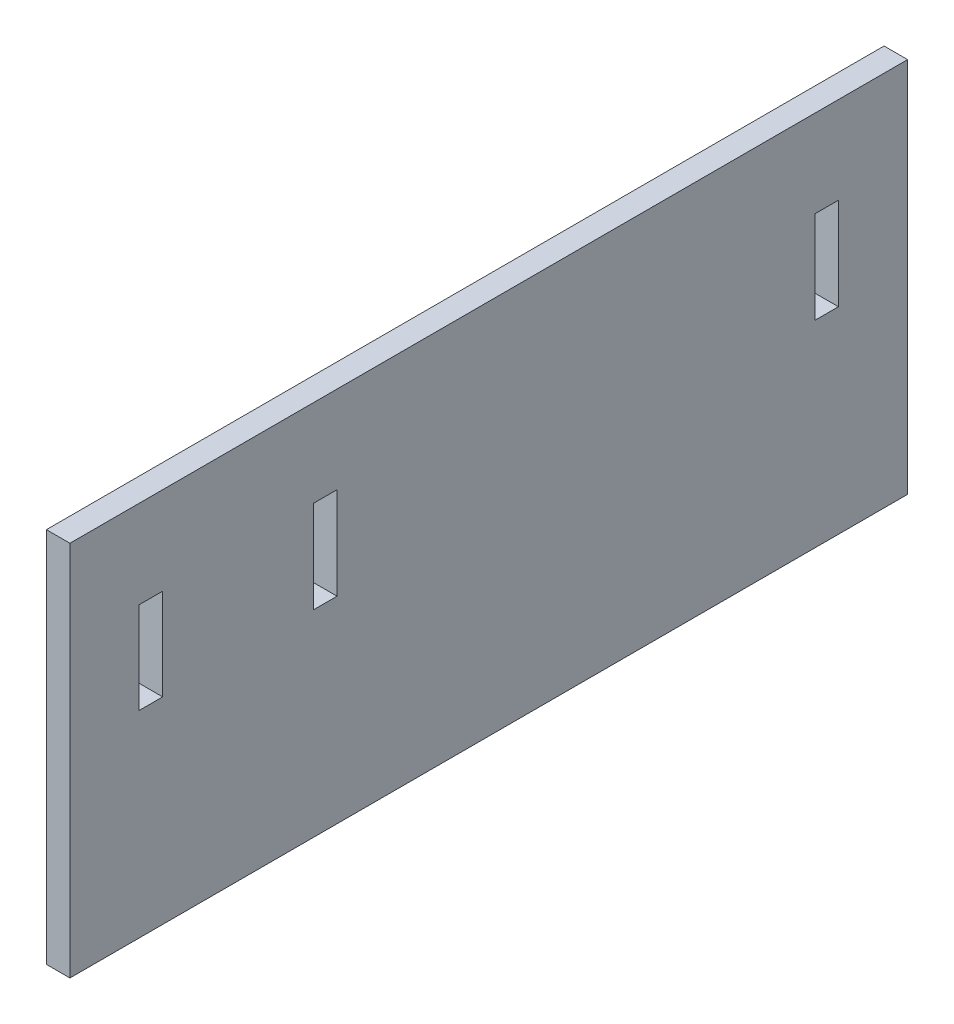
SolidWorks part; units mm, degrees
ref_plane "Front Plane" through (0, 0, 0) normal (0, 0, 1) x (1, 0, 0)
ref_plane "Top Plane" through (0, 0, 0) normal (0, 1, 0) x (1, 0, 0)
ref_plane "Right Plane" through (0, 0, 0) normal (1, 0, 0) x (0, 0, -1)
sketch "Sketch1" plane through (0, 0, 0) normal (1, 0, 0) x (0, 0, -1)
  line L0 (6.775, 20.4226) -> (9.475, 20.4226) construction
  line L1 (6.775, 9.9226) -> (9.475, 9.9226)
  line L2 (9.475, 9.9226) -> (9.475, 20.4226)
  line L3 (9.475, 20.4226) -> (6.775, 20.4226)
  line L4 (6.775, 9.9226) -> (9.475, 9.9226) construction
  line L5 (3.2125, 30.5) -> (83.4125, 30.5)
  line L7 (86.975, 20.5018) -> (84.275, 20.5018)
  line L8 (84.275, 20.5018) -> (84.275, 9.9226)
  line L9 (84.275, 9.9226) -> (86.975, 9.9226)
  line L11 (86.975, -12.68) -> (6.775, -12.68)
  line L13 (26.775, 20.5018) -> (29.475, 20.5018)
  line L14 (26.775, 20.5018) -> (26.775, 9.9226)
  line L15 (26.775, 9.9226) -> (29.475, 9.9226)
  line L16 (29.475, 20.5018) -> (29.475, 9.9226)
  line L17 (3.2125, 30.5) -> (-1.1625, 30.5)
  line L18 (6.775, 20.4226) -> (6.775, 9.9226)
  line L19 (6.775, -12.68) -> (-1.1625, -12.68)
  line L20 (-1.1625, 30.5) -> (-1.1625, -12.68)
  line L21 (83.4125, 30.5) -> (94.9125, 30.5)
  line L22 (86.975, 20.5018) -> (86.975, 9.9226)
  line L23 (86.975, -12.68) -> (94.9125, -12.68)
  line L24 (94.9125, 30.5) -> (94.9125, -12.68)
  line L28 (26.775, 20.5018) -> (29.475, 20.5018) construction
  point P18 (28.125, 9.9226)
  point P19 (8.125, 9.9226)
  point P20 (85.625, 9.9226)
  dimension "D1" = 2.7
  dimension "D2" = 43.18
  dimension "D4" = 7.9375
  dimension "D5" = 20
  dimension "D6" = 57.5
  dimension "D7" = 7.9375
extrude "Panel" add sketch "Sketch1" along normal blind 2.7
